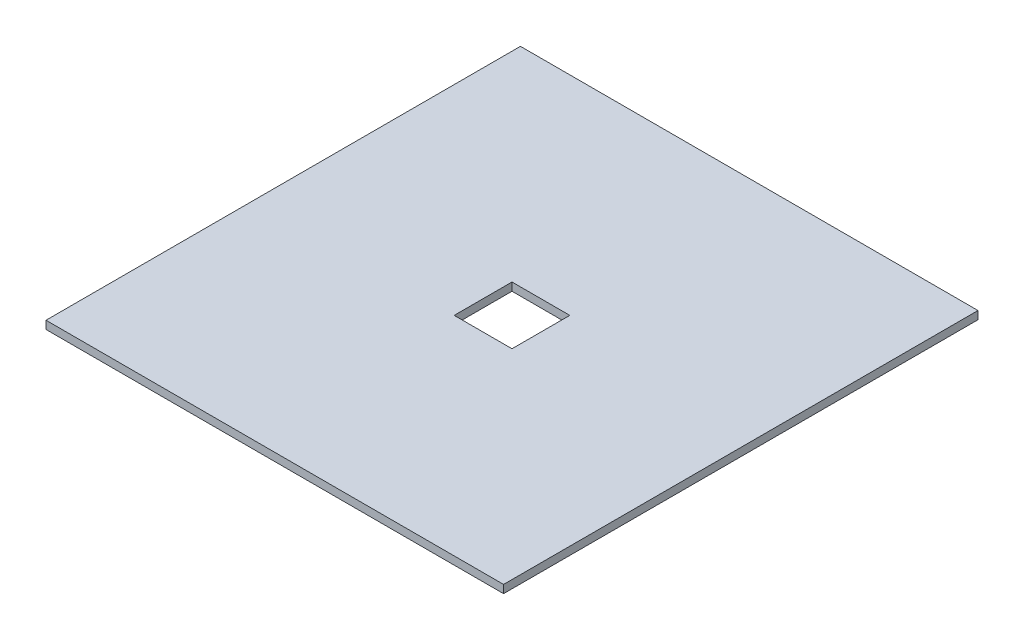
SolidWorks part; units mm, degrees
ref_plane "Front" through (0, 0, 0) normal (0, 0, 1) x (1, 0, 0)
ref_plane "Top" through (0, 0, 0) normal (0, 1, 0) x (1, 0, 0)
ref_plane "Right" through (0, 0, 0) normal (1, 0, 0) x (0, 0, -1)
sketch "Sketch1" plane through (0, 0, 0) normal (0, 1, 0) x (1, 0, 0)
  line L1 (-90.4875, -93.8212) -> (90.4875, -93.8212)
  line L2 (-90.4875, -93.8212) -> (-90.4875, 93.8212)
  line L3 (-90.4875, 93.8212) -> (90.4875, 93.8212)
  line L4 (90.4875, -93.8212) -> (90.4875, 93.8212)
  line L5 (-90.4875, -93.8212) -> (90.4875, 93.8212) construction
  line L6 (-90.4875, 93.8212) -> (90.4875, -93.8212) construction
  point P0 (0, 0)
  dimension "D1" = 180.975
  dimension "D2" = 187.6425
extrude "Boss-Extrude1" add sketch "Sketch1" along normal blind 3.175
sketch "Sketch2" plane through (0, 3.175, 0) normal (0, 1, 0) x (1, 0, 0)
  line L0 (-90.4875, 93.8212) -> (90.4875, -93.8212) construction
  line L2 (-11.43, -11.43) -> (11.43, -11.43)
  line L3 (-11.43, -11.43) -> (-11.43, 11.43)
  line L4 (-11.43, 11.43) -> (11.43, 11.43)
  line L5 (11.43, -11.43) -> (11.43, 11.43)
  line L6 (-11.43, -11.43) -> (11.43, 11.43) construction
  line L7 (-11.43, 11.43) -> (11.43, -11.43) construction
  point P4 (0, 0)
  dimension "D1" = 22.86
extrude "Cut-Extrude1" cut sketch "Sketch2" against normal blind 3.175
